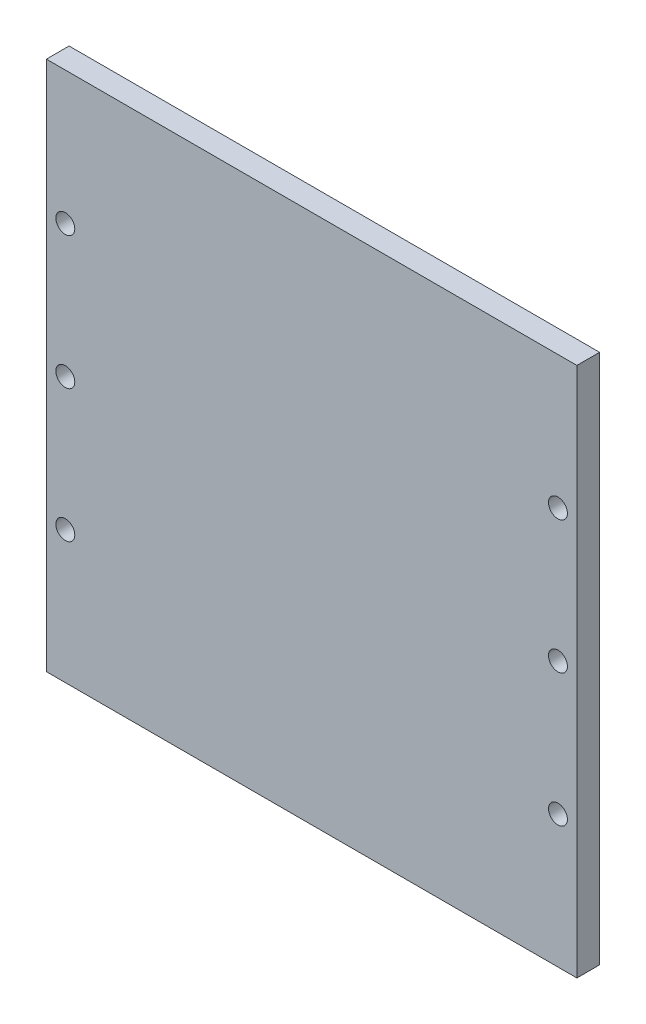
SolidWorks part; units mm, degrees
ref_plane "Front Plane" through (0, 0, 0) normal (0, 0, 1) x (1, 0, 0)
ref_plane "Top Plane" through (0, 0, 0) normal (0, 1, 0) x (1, 0, 0)
ref_plane "Right Plane" through (0, 0, 0) normal (1, 0, 0) x (0, 0, -1)
sketch "Sketch1" plane through (0, 0, 0) normal (0, 0, 1) x (1, 0, 0)
  line L1 (-35.585, 35.585) -> (35.585, 35.585)
  line L2 (-35.585, 35.585) -> (-35.585, -35.585)
  line L3 (-35.585, -35.585) -> (35.585, -35.585)
  line L4 (35.585, 35.585) -> (35.585, -35.585)
  line L5 (-35.585, 35.585) -> (35.585, -35.585) construction
  line L6 (-35.585, -35.585) -> (35.585, 35.585) construction
  point P0 (0, 0)
  dimension "D1" = 71.17
  dimension "D2" = 71.17
extrude "Boss-Extrude1" add sketch "Sketch1" along normal blind 3.048
sketch "Sketch2" plane through (0, 0, 3.048) normal (0, 0, 1) x (1, 0, 0)
  line L0 (35.585, -35.585) -> (35.585, 35.585) construction
  line L1 (-35.585, -35.585) -> (35.585, -35.585) construction
  line L2 (35.585, 35.585) -> (-35.585, 35.585) construction
  circle A0 centre (33.045, -17.805) radius 1.27
  circle A1 centre (33.045, -0.025) radius 1.27
  circle A2 centre (33.045, 17.755) radius 1.27
  circle A3 centre (-33.045, -17.805) radius 1.27
  circle A4 centre (-33.045, -0.025) radius 1.27
  circle A5 centre (-33.045, 17.755) radius 1.27
  point P18 (0, 34.7621)
  dimension "D1" = 2.54
  dimension "D2" = 2.54
  dimension "D3" = 17.78
  dimension "D6" = 17.83
  dimension "D4" = 35.56
  dimension "D5" = 53.34
extrude "Cut-Extrude2" cut sketch "Sketch2" against normal blind 10
